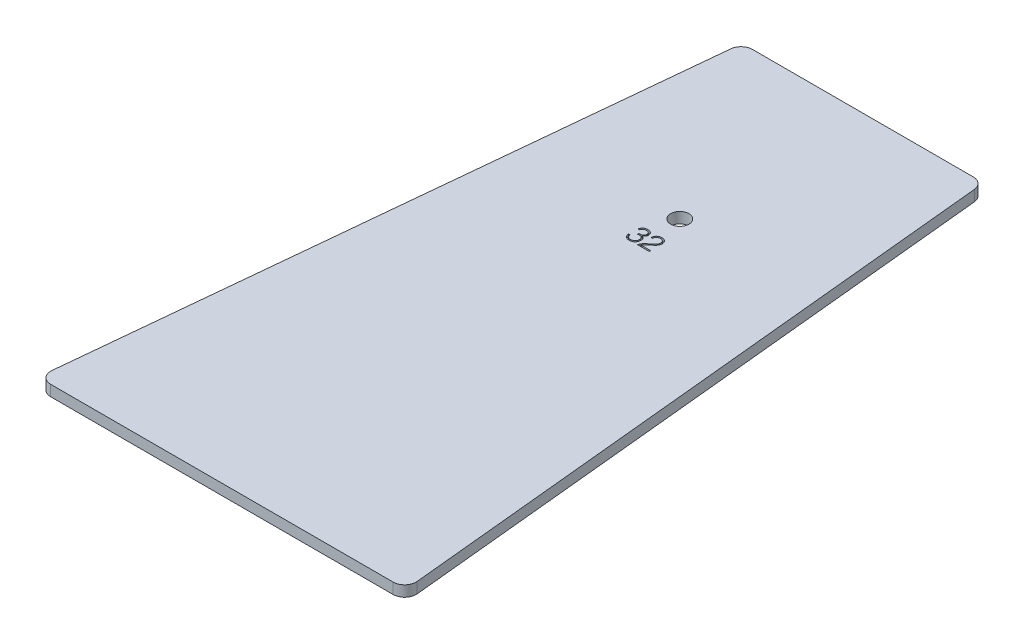
SolidWorks part; units mm, degrees
material "Acrylic (Medium-high impact)"
ref_plane "Front Plane" through (0, 0, 0) normal (0, 0, 1) x (1, 0, 0)
ref_plane "Top Plane" through (0, 0, 0) normal (0, 1, 0) x (1, 0, 0)
ref_plane "Right Plane" through (0, 0, 0) normal (1, 0, 0) x (0, 0, -1)
sketch "Sketch1" plane through (0, 0, 0) normal (0, 1, 0) x (1, 0, 0)
  line L0 (0, 0) -> (0, -355.6) construction
  line L1 (-66.9925, 0) -> (66.9925, 0)
  line L2 (66.9925, 0) -> (102.016, -355.6)
  line L3 (102.016, -355.6) -> (-102.016, -355.6)
  line L4 (-66.9925, 0) -> (-102.016, -355.6)
  dimension "D1" = 355.6
  dimension "D2" = 11.25
  dimension "D3" = 133.985
extrude "Boss-Extrude1" add sketch "Sketch1" along normal blind 5.9944
sketch "Sketch2" plane through (0, 5.9944, 0) normal (0, 1, 0) x (1, 0, 0)
  line L0 (0, 0) -> (0, -101.6) construction
  line L1 (66.9925, 0) -> (-66.9925, 0) construction
  circle A0 centre (0, -101.6) radius 5.08
  dimension "D2" = 10.16
  dimension "D1" = 101.6
extrude "Cut-Extrude1" cut sketch "Sketch2" against normal through all
sketch "Sketch3" plane through (0, 5.9944, 0) normal (0, 1, 0) x (1, 0, 0)
  line L0 (0, 0) -> (0, -114.3) construction
  line L1 (-7.62, -125.73) -> (7.62, -125.73) construction
  line L2 (-7.62, -125.73) -> (-7.62, -114.3) construction
  line L3 (-7.62, -114.3) -> (7.62, -114.3) construction
  line L4 (7.62, -125.73) -> (7.62, -114.3) construction
  line L5 (66.9925, 0) -> (-66.9925, 0) construction
  text T0 "32"
  dimension "D1" = 11.43
  dimension "D2" = 114.3
  dimension "D3" = 15.24
extrude "Cut-Extrude2" cut sketch "Sketch3" against normal blind 1.27
fillet "Fillet1" radius 6.35 4 edges at (102.016, 2.9972, 355.6) (-102.016, 2.9972, 355.6) (-66.9925, 2.9972, 0) (66.9925, 2.9972, 0)
move or copy body "Body-Move/Copy1" [suppressed] bodies to move or copy 103 copy no rotation origin (0, 0, 177.8) rotation axis (0, 1, 0) rotation angle 90
